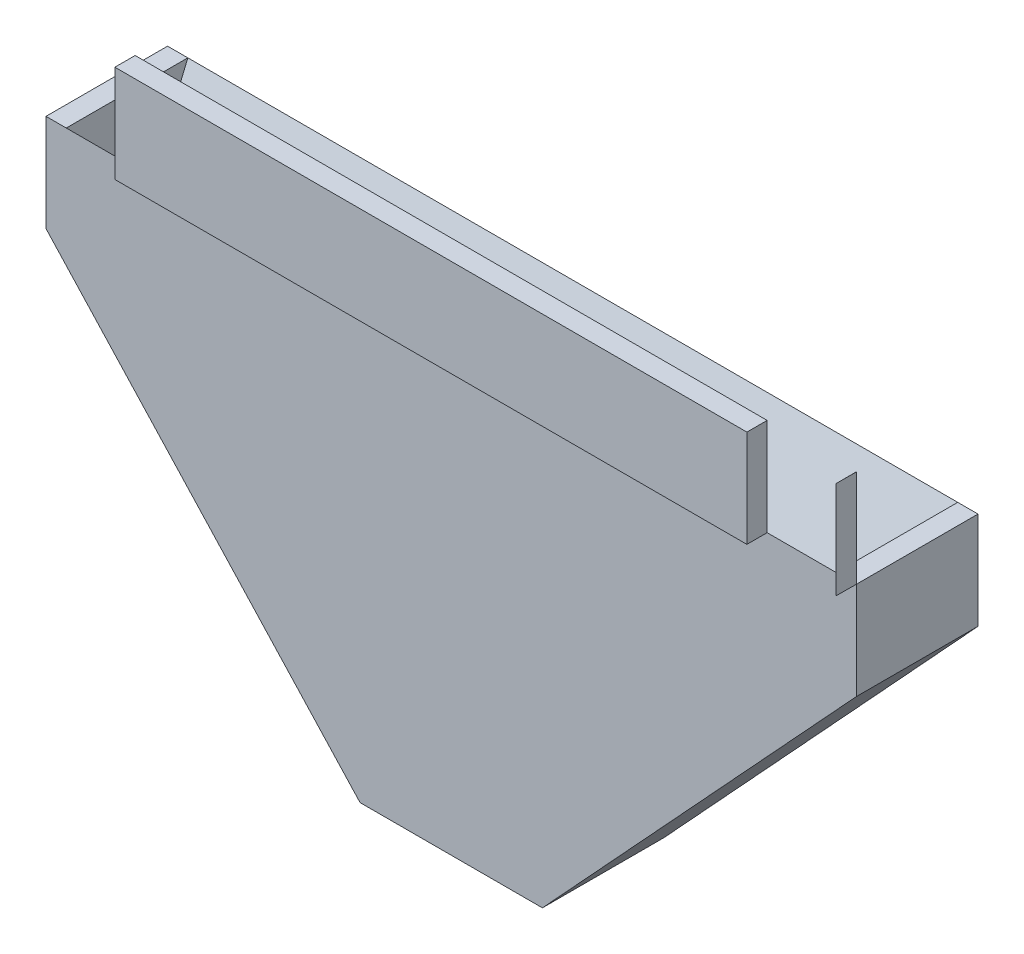
SolidWorks part; units mm, degrees
ref_plane "Front Plane" through (0, 0, 0) normal (0, 0, 1) x (1, 0, 0)
ref_plane "Top Plane" through (0, 0, 0) normal (0, 1, 0) x (1, 0, 0)
ref_plane "Right Plane" through (0, 0, 0) normal (1, 0, 0) x (0, 0, -1)
sketch "Sketch1" plane through (0, 0, 0) normal (0, 0, 1) x (1, 0, 0)
  line L0 (0, 0) -> (200, 0)
  line L1 (200, 0) -> (200, -24)
  line L2 (200, -24) -> (0, -24)
  line L3 (0, -24) -> (0, 0)
  dimension "D1" = 200
  dimension "D2" = 24
extrude "Boss-Extrude1" add sketch "Sketch1" along normal blind 30
sketch "Sketch2" plane through (200, 0, 0) normal (1, 0, 0) x (0, 0, -1)
  line L0 (-30, 0) -> (-20, -24)
  line L1 (-30, -24) -> (0, -24) construction
  line L2 (-20, -24) -> (-10, -24)
  line L3 (-10, -24) -> (0, 0)
  line M2 (0, 0) -> (-30, 0)
  line M4 (-30, -24) -> (0, -24)
  dimension "D1" = 10
  dimension "D2" = 10
extrude "Cut-Extrude1" cut sketch "Sketch2" against normal blind 195 and the other way through all contours L3 L0 M4 M2
sketch "Sketch3" plane through (0, -24, 0) normal (0, -1, 0) x (-1, 0, 0)
  line L0 (-200, -30) -> (-195, -30)
  line L1 (0, -30) -> (-200, -30) construction
  line L2 (-195, -30) -> (-195, 0)
  line L3 (0, 0) -> (-200, 0) construction
  line L4 (-195, 0) -> (-200, 0)
  line L5 (-200, 0) -> (-200, -30)
  dimension "D1" = 5
extrude "Boss-Extrude2" add sketch "Sketch3" against normal blind 24
sketch "Sketch5" plane through (0, 0, 0) normal (0, 1, 0) x (1, 0, 0)
  line L0 (0, -30) -> (0, -35)
  line L1 (0, -35) -> (199.9674, -35)
  line L2 (199.9674, -35) -> (200, -30)
  line L3 (200, -30) -> (0, -30)
  dimension "D1" = 5
extrude "Boss-Extrude3" add sketch "Sketch5" along normal blind 24 separate body
sketch "Sketch6" plane through (0, 0, 30) normal (0, 0, -1) x (-1, 0, 0)
  line L0 (-200, 24) -> (0, 24) construction
  line L2 (-195, 0) -> (-5, 0) construction
  circle A0 centre (-189.7456, 10.82) radius 2.005
  circle A2 centre (-169.4856, 10.82) radius 2.005
  circle A3 centre (-149.2256, 10.82) radius 2.005
  circle A4 centre (-128.9656, 10.82) radius 2.005
  circle A5 centre (-108.7056, 10.82) radius 2.005
  circle A6 centre (-88.4456, 10.82) radius 2.005
  circle A7 centre (-68.1856, 10.82) radius 2.005
  circle A8 centre (-47.9256, 10.82) radius 2.005
  circle A9 centre (-27.6656, 10.82) radius 2.005
  circle A10 centre (-7.4056, 10.82) radius 2.005
  circle A11 centre (12.8544, 10.82) radius 2.005
  dimension "D2" = 4.01
  dimension "D4" = 11
  dimension "D5" = 20.26
  dimension "D1" = 13.18
  dimension "D3" = 10.82
sketch "Sketch10" plane through (0, 0, 35) normal (0, 0, 1) x (1, 0, 0)
  line L1 (199.9674, 0) -> (177.9674, 0)
  line L2 (0, 0) -> (199.9674, 0) construction
  line L3 (177.9674, 0) -> (177.9674, 24)
  line L4 (0, 24) -> (199.9674, 24) construction
  line L5 (177.9674, 24) -> (199.9674, 24)
  line L6 (177.9674, 24) -> (209.5944, 24)
  line L7 (209.5944, 24) -> (209.5944, 0)
  line L8 (209.5944, 0) -> (177.9674, 0)
  line M2 (199.9674, 24) -> (0, 24)
  line M4 (0, 0) -> (199.9674, 0)
  line M5 (199.9674, 0) -> (199.9674, 24)
  dimension "D1" = 22
extrude "Cut-Extrude8" cut sketch "Sketch10" against normal blind 24 contours L3 M4 M5 M2
sketch "Sketch12" plane through (0, 0, 30) normal (0, 0, -1) x (-1, 0, 0)
  line L0 (0, 24) -> (-22, 24)
  line L1 (-177.9674, 24) -> (0, 24) construction
  line L2 (-22, 24) -> (-22, 0)
  line L3 (-195, 0) -> (-5, 0) construction
  line L4 (-22, 0) -> (0, 0)
  line L5 (0, 0) -> (0, 24)
  dimension "D1" = 22
extrude "Cut-Extrude9" cut sketch "Sketch12" against normal blind 24
sketch "Sketch13" plane through (0, 0, 0) normal (0, 0, -1) x (-1, 0, 0)
  line L0 (-200, -24) -> (-122.5, -107.9192)
  line L1 (-122.5, -107.9192) -> (-77.5, -107.9192)
  line L2 (-77.5, -107.9192) -> (0, -24)
  line L3 (0, -24) -> (-100, -24)
  line L4 (0, -24) -> (-200, -24) construction
  line L11 (-5, 0) -> (-195, 0)
  line L12 (-195, 0) -> (-200, 0)
  line L13 (-200, 0) -> (-200, -24)
  line L14 (-200, -24) -> (0, -24)
  line L15 (0, -24) -> (0, 0)
  line L16 (0, 0) -> (-5, 0)
  line L20 (-200, -24) -> (-100, -24)
  dimension "D1" = 0
  dimension "D2" = 45
extrude "Boss-Extrude4" add sketch "Sketch13" against normal blind 30
sketch "Sketch15" plane through (0, 0, 0) normal (0, 0, -1) x (-1, 0, 0)
  line L0 (-200, -24) -> (0, -24) construction
  line L1 (-195, -24) -> (-117.5, -107.9192)
  line L2 (-122.5, -107.9192) -> (-77.5, -107.9192) construction
  line L3 (-117.5, -107.9192) -> (-82.5, -107.9192)
  line L4 (-82.5, -107.9192) -> (-5, -24)
  line L5 (-5, -24) -> (-195, -24)
  line M9 (-122.5, -107.9192) -> (-77.5, -107.9192)
  dimension "D1" = 5
  dimension "D2" = 5
  dimension "D3" = 5
  dimension "D4" = 5
extrude "Cut-Extrude13" cut sketch "Sketch15" against normal blind 20 contours L4 L5 L1 M9
sketch "Sketch16" plane through (0, -24, 0) normal (0, -1, 0) x (1, 0, 0)
  line L0 (5, 0) -> (195, 0)
  line L1 (200, 0) -> (122.5, 0) construction
  line L2 (195, 0) -> (195, 10)
  line L3 (195, 10) -> (5, 10)
  line L4 (195, 10) -> (5, 10) construction
  line L5 (5, 10) -> (5, 0)
  line L6 (0, 30) -> (0, 0) construction
  line L7 (200, 30) -> (200, 0) construction
  dimension "D1" = 5
  dimension "D2" = 5
extrude "Boss-Extrude5" add sketch "Sketch16" along normal blind 84
sketch "Sketch17" plane through (0, 0, 10) normal (0, 0, 1) x (1, 0, 0)
  line L0 (5, -29.4141) -> (77.5, -107.9192)
  line L2 (5, -108) -> (5, -29.4141)
  line L3 (5, -108) -> (5, -132.2899)
  line L4 (5, -132.2899) -> (77.5, -132.2899)
  line L5 (77.5, -132.2899) -> (77.5, -107.9192)
extrude "Cut-Extrude15" cut sketch "Sketch17" against normal blind 84
sketch "Sketch18" plane through (0, 0, 10) normal (0, 0, 1) x (1, 0, 0)
  line L0 (195, -29.4141) -> (122.5, -107.9192)
  line L1 (122.5, -107.9192) -> (122.8565, -124.2094)
  line L2 (122.8565, -124.2094) -> (195, -124.2094)
  line L3 (195, -124.2094) -> (195, -29.4141)
extrude "Cut-Extrude16" cut sketch "Sketch18" against normal blind 84
sketch "Sketch19" plane through (0, 0, 10) normal (0, 0, 1) x (1, 0, 0)
  line L0 (77.5, -107.9192) -> (77.5, -108)
  line L1 (77.5, -108) -> (122.5018, -108)
  line L2 (122.5018, -108) -> (122.5, -107.9192)
  line L3 (122.5, -107.9192) -> (77.5, -107.9192)
  line L4 (77.5, -108) -> (77.5, -107.9192)
  line M1 (77.5, -108) -> (122.5018, -108)
  line M2 (122.5018, -108) -> (122.5, -107.9192)
  line M3 (122.5, -107.9192) -> (117.5, -107.9192)
  line M7 (82.5, -107.9192) -> (77.5, -107.9192)
  line M8 (77.5, -107.9192) -> (77.5, -108)
extrude "Cut-Extrude17" cut sketch "Sketch19" against normal blind 84 contours L3 M3 M7 M8 M1 M2
